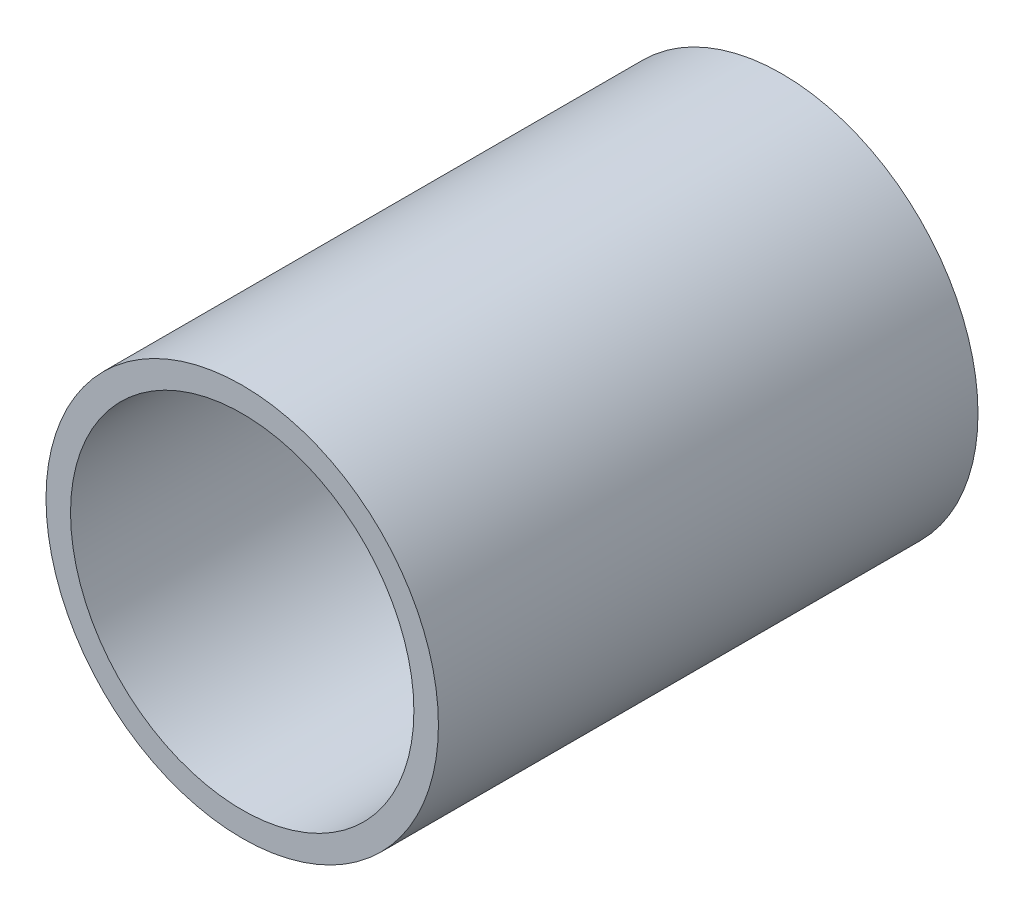
SolidWorks part; units mm, degrees
ref_plane "Front Plane" through (0, 0, 0) normal (0, 0, 1) x (1, 0, 0)
ref_plane "Top Plane" through (0, 0, 0) normal (0, 1, 0) x (1, 0, 0)
ref_plane "Right Plane" through (0, 0, 0) normal (1, 0, 0) x (0, 0, -1)
sketch "Sketch1" plane through (0, 0, 0) normal (0, 0, 1) x (1, 0, 0)
  circle A0 centre (0, 0) radius 35
  circle A1 centre (0, 0) radius 40
  dimension "D1" = 80
  dimension "D2" = 70
extrude "Boss-Extrude1" add sketch "Sketch1" along normal blind 110
